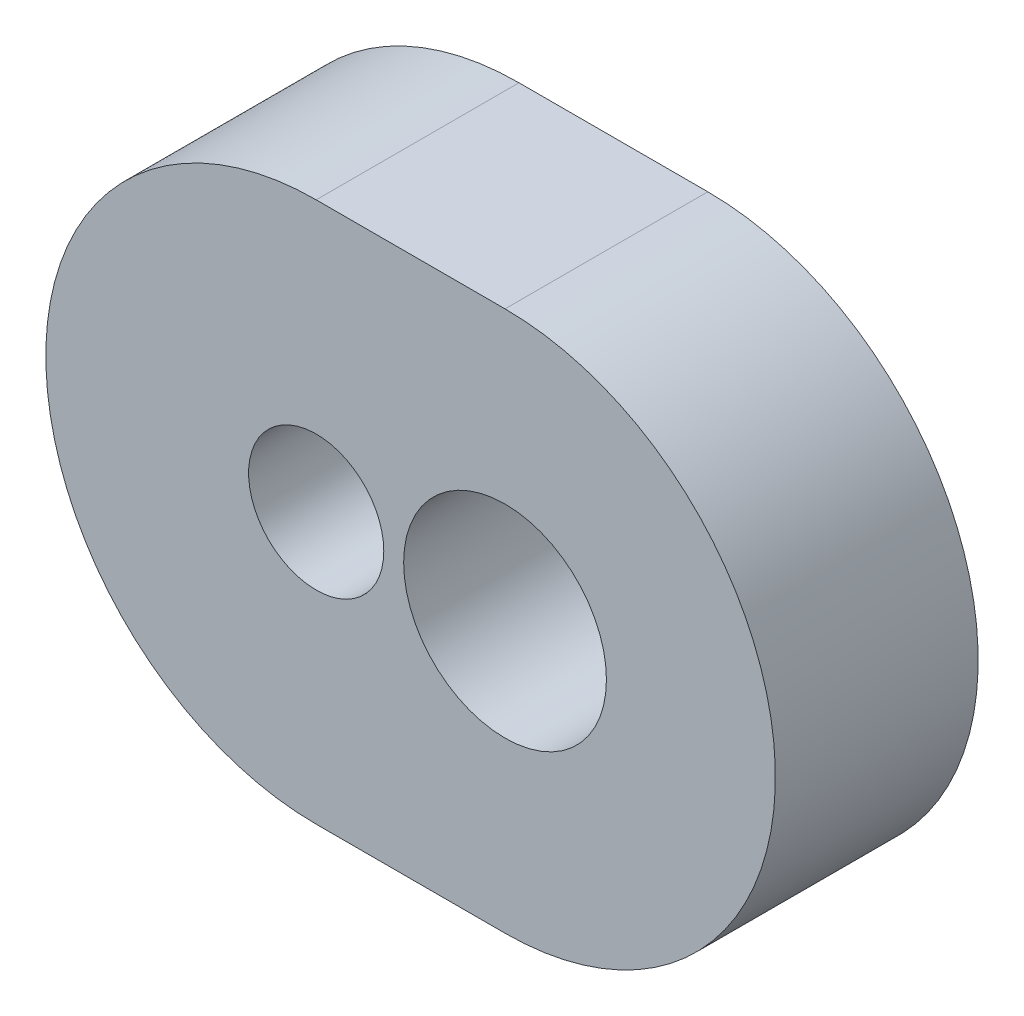
SolidWorks part; units mm, degrees
material "Acrylic (Medium-high impact)"
ref_plane "Front Plane" through (0, 0, 0) normal (0, 0, 1) x (1, 0, 0)
ref_plane "Top Plane" through (0, 0, 0) normal (0, 1, 0) x (1, 0, 0)
ref_plane "Right Plane" through (0, 0, 0) normal (1, 0, 0) x (0, 0, -1)
sketch "스케치1" plane through (0, 0, 0) normal (0, 0, 1) x (1, 0, 0)
  line L0 (0, 2.425) -> (-0.254, 2.2718) construction
  line L1 (-2.794, 4) -> (0, 4)
  line L2 (-2.794, 4) -> (-2.794, -4) construction
  line L3 (-2.794, -4) -> (0, -4)
  line L4 (0, 4) -> (0, -4) construction
  line L5 (-2.794, 4) -> (0, -4) construction
  line L6 (-2.794, -4) -> (0, 4) construction
  line L7 (0, 2.425) -> (0.254, 2.2718) construction
  line L8 (0.6031, 2.3488) -> (0.811, 2.1373) construction
  line L9 (0.6031, 2.3488) -> (0.319, 2.2636) construction
  line L10 (1.1683, 2.125) -> (1.3171, 1.8685) construction
  line L11 (1.1683, 2.125) -> (0.8719, 2.1132) construction
  line L12 (1.66, 1.7677) -> (1.7403, 1.4822) construction
  line L13 (1.66, 1.7677) -> (1.37, 1.83) construction
  line L14 (2.0475, 1.2994) -> (2.0543, 1.0029) construction
  line L15 (2.0475, 1.2994) -> (1.7821, 1.4318) construction
  line L16 (2.3063, 0.7494) -> (2.2391, 0.4605) construction
  line L17 (2.3063, 0.7494) -> (2.0822, 0.9436) construction
  line L18 (2.4202, 0.1523) -> (2.2833, -0.1108) construction
  line L19 (2.4202, 0.1523) -> (2.2514, 0.3961) construction
  line L20 (2.382, -0.4544) -> (2.184, -0.6752) construction
  line L21 (2.382, -0.4544) -> (2.2792, -0.1762) construction
  line L22 (2.1942, -1.0325) -> (1.9475, -1.1971) construction
  line L23 (2.1942, -1.0325) -> (2.1638, -0.7375) construction
  line L24 (1.8685, -1.5458) -> (1.5886, -1.6438) construction
  line L25 (1.8685, -1.5458) -> (1.9124, -1.2524) construction
  line L26 (1.4254, -1.9619) -> (1.1299, -1.9873) construction
  line L27 (1.4254, -1.9619) -> (1.5408, -1.6887) construction
  line L28 (0.8927, -2.2547) -> (0.6002, -2.2058) construction
  line L29 (0.8927, -2.2547) -> (1.0725, -2.0188) construction
  line L30 (0.3039, -2.4059) -> (0.0327, -2.2858) construction
  line L31 (0.3039, -2.4059) -> (0.5367, -2.2221) construction
  line L32 (-0.3039, -2.4059) -> (-0.5367, -2.2221) construction
  line L33 (-0.3039, -2.4059) -> (-0.0327, -2.2858) construction
  line L34 (-0.8927, -2.2547) -> (-1.0725, -2.0188) construction
  line L35 (-0.8927, -2.2547) -> (-0.6002, -2.2058) construction
  line L36 (-1.4254, -1.9619) -> (-1.5408, -1.6887) construction
  line L37 (-1.4254, -1.9619) -> (-1.1299, -1.9873) construction
  line L38 (-1.8685, -1.5458) -> (-1.9124, -1.2524) construction
  line L39 (-1.8685, -1.5458) -> (-1.5886, -1.6438) construction
  line L40 (-2.1942, -1.0325) -> (-2.1638, -0.7375) construction
  line L41 (-2.1942, -1.0325) -> (-1.9475, -1.1971) construction
  line L42 (-2.382, -0.4544) -> (-2.2792, -0.1762) construction
  line L43 (-2.382, -0.4544) -> (-2.184, -0.6752) construction
  line L44 (-2.4202, 0.1523) -> (-2.2514, 0.3961) construction
  line L45 (-2.4202, 0.1523) -> (-2.2833, -0.1108) construction
  line L46 (-2.3063, 0.7494) -> (-2.0822, 0.9436) construction
  line L47 (-2.3063, 0.7494) -> (-2.2391, 0.4605) construction
  line L48 (-2.0475, 1.2994) -> (-1.7821, 1.4318) construction
  line L49 (-2.0475, 1.2994) -> (-2.0543, 1.0029) construction
  line L50 (-1.66, 1.7677) -> (-1.37, 1.83) construction
  line L51 (-1.66, 1.7677) -> (-1.7403, 1.4822) construction
  line L52 (-1.1683, 2.125) -> (-0.8719, 2.1132) construction
  line L53 (-1.1683, 2.125) -> (-1.3171, 1.8685) construction
  line L54 (-0.6031, 2.3488) -> (-0.319, 2.2636) construction
  line L55 (-0.6031, 2.3488) -> (-0.811, 2.1373) construction
  line L56 (0.254, 2.2718) -> (-0.254, 2.2718) construction
  circle A0 centre (0, 0) radius 2.425 construction
  circle A1 centre (0, 0) radius 4 construction
  circle A2 centre (-2.794, 0) radius 4 construction
  circle A3 centre (-2.794, 0) radius 1
  arc A4 (-2.794, 4) -> (-2.794, -4) centre (-2.794, 0) ccw
  arc A5 (0, 4) -> (0, -4) centre (0, 0) cw
  arc A6 (-0.254, 2.2718) -> (-0.319, 2.2636) centre (0, 0) ccw construction
  arc A7 (-0.811, 2.1373) -> (-0.8719, 2.1132) centre (0, 0) ccw construction
  arc A8 (-1.3171, 1.8685) -> (-1.37, 1.83) centre (0, 0) ccw construction
  arc A9 (-1.7403, 1.4822) -> (-1.7821, 1.4318) centre (0, 0) ccw construction
  arc A10 (-2.0543, 1.0029) -> (-2.0822, 0.9436) centre (0, 0) ccw construction
  arc A11 (-2.2391, 0.4605) -> (-2.2514, 0.3961) centre (0, 0) ccw construction
  arc A12 (-2.2833, -0.1108) -> (-2.2792, -0.1762) centre (0, 0) ccw construction
  arc A13 (-2.184, -0.6752) -> (-2.1638, -0.7375) centre (0, 0) ccw construction
  arc A14 (-1.9475, -1.1971) -> (-1.9124, -1.2524) centre (0, 0) ccw construction
  arc A15 (-1.5886, -1.6438) -> (-1.5408, -1.6887) centre (0, 0) ccw construction
  arc A16 (-1.1299, -1.9873) -> (-1.0725, -2.0188) centre (0, 0) ccw construction
  arc A17 (-0.6002, -2.2058) -> (-0.5367, -2.2221) centre (0, 0) ccw construction
  arc A18 (-0.0327, -2.2858) -> (0.0327, -2.2858) centre (0, 0) ccw construction
  arc A19 (0.5367, -2.2221) -> (0.6002, -2.2058) centre (0, 0) ccw construction
  arc A20 (1.0725, -2.0188) -> (1.1299, -1.9873) centre (0, 0) ccw construction
  arc A21 (1.5408, -1.6887) -> (1.5886, -1.6438) centre (0, 0) ccw construction
  arc A22 (1.9124, -1.2524) -> (1.9475, -1.1971) centre (0, 0) ccw construction
  arc A23 (2.1638, -0.7375) -> (2.184, -0.6752) centre (0, 0) ccw construction
  arc A24 (2.2792, -0.1762) -> (2.2833, -0.1108) centre (0, 0) ccw construction
  arc A25 (2.2514, 0.3961) -> (2.2391, 0.4605) centre (0, 0) ccw construction
  arc A26 (2.0822, 0.9436) -> (2.0543, 1.0029) centre (0, 0) ccw construction
  arc A27 (1.7821, 1.4318) -> (1.7403, 1.4822) centre (0, 0) ccw construction
  arc A28 (1.37, 1.83) -> (1.3171, 1.8685) centre (0, 0) ccw construction
  arc A29 (0.8719, 2.1132) -> (0.811, 2.1373) centre (0, 0) ccw construction
  arc A30 (0.319, 2.2636) -> (0.254, 2.2718) centre (0, 0) ccw construction
  circle A31 centre (0, 0) radius 1.5
  point P4 (-1.397, 0)
  point P93 (0, 0)
  dimension "D1" = 4.85
  dimension "D2" = 3
  dimension "D3" = 2
  dimension "D5" = 25
  dimension "D7" = 4.572
  dimension "D8" = 3
  dimension "D4" = 2.794
  dimension "D6" = 0.508
extrude "보스-돌출1" add sketch "스케치1" along normal blind 3
